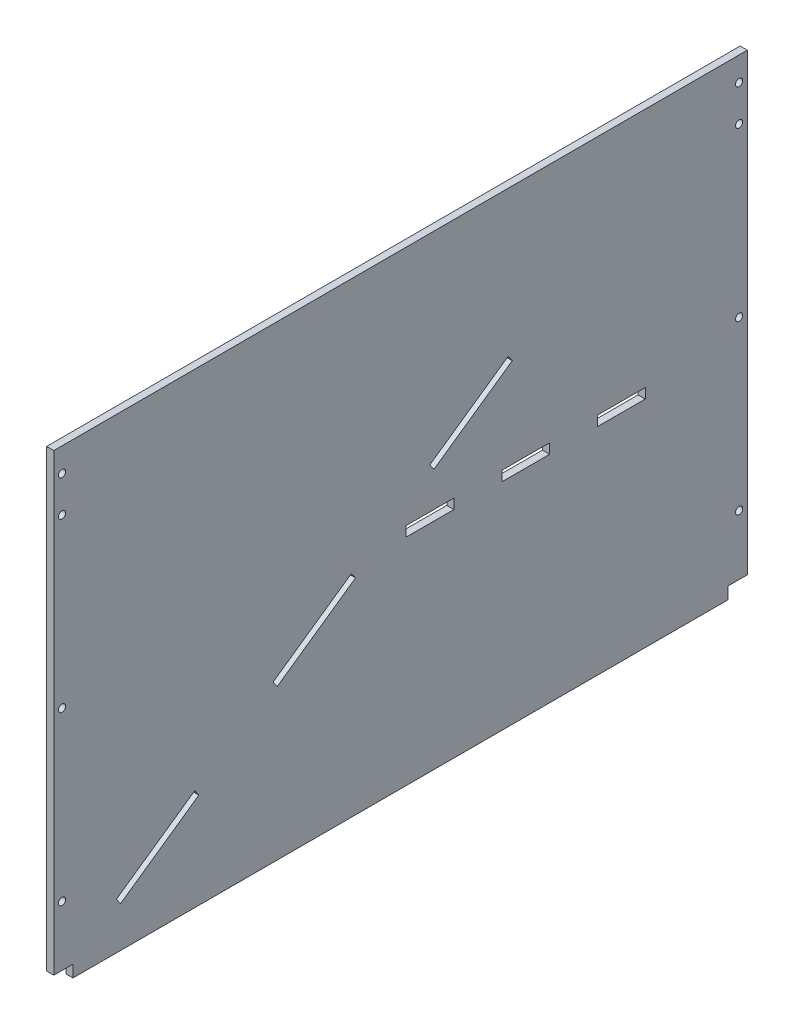
SolidWorks part; units mm, degrees
ref_plane "Front Plane" through (0, 0, 0) normal (0, 0, 1) x (1, 0, 0)
ref_plane "Top Plane" through (0, 0, 0) normal (0, 1, 0) x (1, 0, 0)
ref_plane "Right Plane" through (0, 0, 0) normal (1, 0, 0) x (0, 0, -1)
sketch "Sketch1" plane through (0, 0, 0) normal (1, 0, 0) x (0, 0, -1)
  line L0 (-159.4695, -9.133) -> (164.4649, -9.133) construction
  line L1 (-149.5, 100.8415) -> (140.5, 100.8415)
  line L2 (-149.5, 100.8415) -> (-149.5, -94.1585)
  line L3 (-149.5, -94.1585) -> (140.5, -94.1585)
  line L4 (140.5, 100.8415) -> (140.5, -94.1585)
  line L52 (-4.5, 100.8415) -> (-4.5, -94.1585) construction
  line L77 (-164.4613, -89.1585) -> (136.7736, -89.1585) construction
  dimension "D1" = 290
  dimension "D6" = 195
  dimension "D37" = 5
extrude "Boss-Extrude1" add sketch "Sketch1" along normal blind 3
sketch "Sketch2" plane through (3, 0, 0) normal (1, 0, 0) x (0, 0, -1)
  line L0 (-169.4926, -89.1585) -> (134.7595, -89.1585) construction
  line L1 (-4.5, 100.8415) -> (-4.5, -113.2176) construction
  line L2 (140.5, 100.8415) -> (-149.5, 100.8415) construction
  line L3 (-141.5, -94.1585) -> (-141.5, -89.1585)
  line L4 (-149.5, -94.1585) -> (140.5, -94.1585) construction
  line L5 (-141.5, -89.1585) -> (-159.4276, -89.1585)
  line L6 (-159.4276, -89.1585) -> (-159.4276, -110.9956)
  line L7 (-159.4276, -110.9956) -> (-141.5, -110.9956)
  line L8 (-141.5, -110.9956) -> (-141.5, -94.1585)
  line L9 (-149.5, 100.8415) -> (-149.5, -94.1585) construction
  line L10 (132.5, -110.9956) -> (132.5, -94.1585)
  line L11 (150.4276, -110.9956) -> (132.5, -110.9956)
  line L12 (150.4276, -89.1585) -> (150.4276, -110.9956)
  line L13 (132.5, -89.1585) -> (150.4276, -89.1585)
  line L14 (132.5, -94.1585) -> (132.5, -89.1585)
  line L15 (140.5, -94.1585) -> (140.5, 100.8415) construction
  dimension "D1" = 5
  dimension "D2" = 8
  dimension "D3" = 8
extrude "Cut-Extrude1" cut sketch "Sketch2" against normal blind 10
sketch "Sketch3" plane through (0, 0, 0) normal (-1, 0, 0) x (0, 0, 1)
  line L0 (150.5, -64.1585) -> (-140, -64.1585) construction
  line L1 (150.5, -76.1585) -> (150.5, 105.8415) construction
  line L2 (-140, -76.1585) -> (-140, 105.8415) construction
  line L3 (149.5, 100.8415) -> (149.5, -89.1585) construction
  circle A0 centre (146.0663, -64.1585) radius 1.5
  circle A1 centre (-137.0618, -64.1585) radius 1.5
  circle A2 centre (-137.0618, 5.8415) radius 1.5
  circle A3 centre (146.0663, 5.8415) radius 1.5
  circle A4 centre (-137.0618, 75.8415) radius 1.5
  circle A5 centre (146.0663, 75.8415) radius 1.5
  circle A6 centre (-137.0618, 90.8415) radius 1.5
  circle A7 centre (146.0663, 90.8415) radius 1.5
  point P24 (0, 0)
  dimension "D2" = 3
  dimension "D4" = 15
  dimension "D5" = 3
  dimension "D3" = 15
  dimension "D6" = 3.4337
  dimension "D1" = 3
extrude "Cut-Extrude2" cut sketch "Sketch3" against normal blind 10
sketch "Sketch4" plane through (3, 0, 0) normal (1, 0, 0) x (0, 0, -1)
  line L0 (-138, -88.6554) -> (58.5965, 49.003) construction
  line L1 (-153, -99.1585) -> (96.11, -99.1585) construction
  line L2 (-139.7207, -86.1979) -> (56.8758, 51.4604) construction
  line L3 (40.4927, 39.9889) -> (42.2134, 37.5314)
  line L4 (56.8758, 51.4604) -> (58.5965, 49.003)
  line L5 (7.7266, 17.0458) -> (9.4474, 14.5884)
  line L6 (-25.0394, -5.8972) -> (-23.3187, -8.3547)
  line L7 (-57.8055, -28.8403) -> (-56.0848, -31.2977)
  line L8 (-90.5716, -51.7834) -> (-88.8509, -54.2408)
  line L9 (-123.3377, -74.7264) -> (-121.617, -77.1839)
  line L10 (-139.7207, -86.1979) -> (-138, -88.6554)
  line L11 (-154.7207, -96.701) -> (56.8758, 51.4604) construction
  line L12 (-153, -99.1585) -> (58.5965, 49.003) construction
  line L13 (-143, -94.1585) -> (-143, 105.8415) construction
  line L15 (42.2134, 37.5314) -> (9.4474, 14.5884)
  line L16 (-23.3187, -8.3547) -> (-56.0848, -31.2977)
  line L17 (-88.8509, -54.2408) -> (-121.617, -77.1839)
  line L18 (-123.3377, -74.7264) -> (-90.5716, -51.7834)
  line L19 (-57.8055, -28.8403) -> (-25.0394, -5.8972)
  line L20 (7.7266, 17.0458) -> (40.4927, 39.9889)
  dimension "D1" = 35
  dimension "D2" = 3
  dimension "D3" = 40
  dimension "D4" = 20
  dimension "D5" = 40
  dimension "D6" = 40
  dimension "D7" = 40
  dimension "D8" = 40
  dimension "D9" = 20
  dimension "D10" = 5
extrude "Cut-Extrude3" cut sketch "Sketch4" against normal blind 10 contours L18 L9 L17 L8 | L19 L7 L16 L6 | L20 L5 L15 L3
sketch "Sketch5" plane through (3, 0, 0) normal (1, 0, 0) x (0, 0, -1)
  line L0 (126.0867, -4.1585) -> (-123.3439, -4.1585) construction
  line L1 (146, -94.1585) -> (-155, -94.1585) construction
  line L2 (-15.1835, -18.5137) -> (-15.1835, 25.9881) construction
  line L3 (-2.1835, -18.5137) -> (-2.1835, 25.9881) construction
  line L4 (126.0867, 0) -> (-2.1835, 0) construction
  line L5 (-2.1835, -4.1585) -> (-2.1835, 0)
  line L6 (-2.1835, 0) -> (17.8165, 0)
  line L7 (17.8165, 0) -> (17.8165, -4.1585)
  line L8 (17.8165, -4.1585) -> (-2.1835, -4.1585)
  line L10 (37.8165, 0) -> (57.8165, 0)
  line L11 (37.8165, 0) -> (37.8165, -4.1585)
  line L12 (37.8165, -4.1585) -> (57.8165, -4.1585)
  line L13 (57.8165, 0) -> (57.8165, -4.1585)
  line L14 (77.8165, 0) -> (97.8165, 0)
  line L15 (77.8165, 0) -> (77.8165, -4.1585)
  line L16 (77.8165, -4.1585) -> (97.8165, -4.1585)
  line L17 (97.8165, 0) -> (97.8165, -4.1585)
  dimension "D1" = 90
  dimension "D2" = 13
  dimension "D3" = 20
  dimension "D4" = 20
  dimension "D5" = 20
  dimension "D6" = 20
  dimension "D7" = 20
extrude "Cut-Extrude4" cut sketch "Sketch5" against normal blind 10
